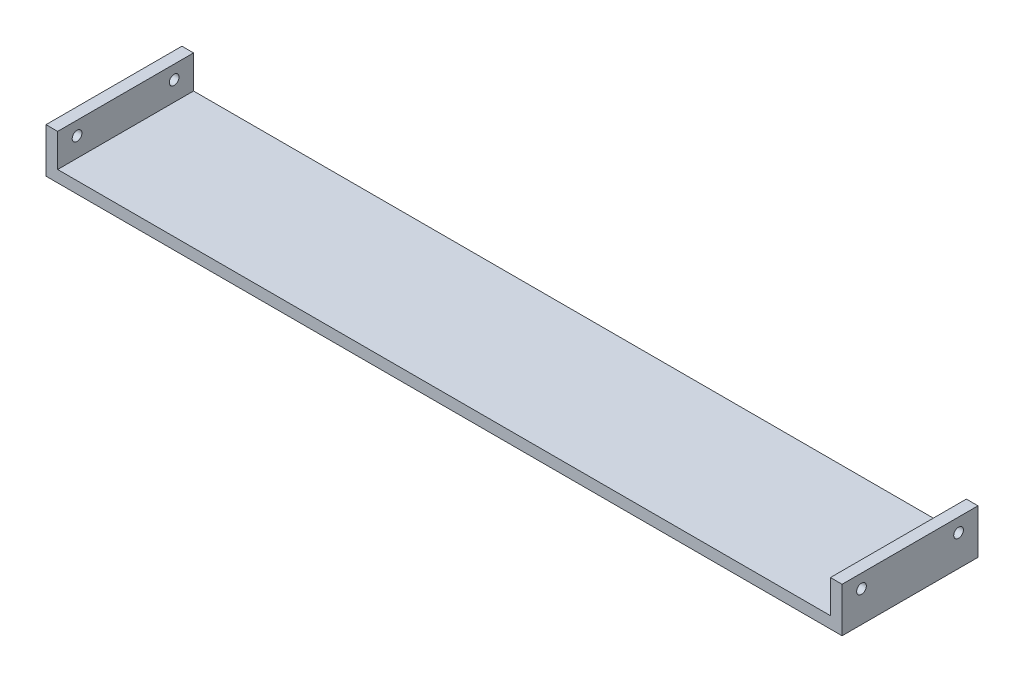
SolidWorks part; units mm, degrees
ref_plane "Front Plane" through (0, 0, 0) normal (0, 0, 1) x (1, 0, 0)
ref_plane "Top Plane" through (0, 0, 0) normal (0, 1, 0) x (1, 0, 0)
ref_plane "Right Plane" through (0, 0, 0) normal (1, 0, 0) x (0, 0, -1)
sketch "Sketch1" plane through (0, 0, 0) normal (0, 1, 0) x (1, 0, 0)
  line L1 (-70.361, 74.6488) -> (339.639, 74.6488)
  line L2 (-70.361, 74.6488) -> (-70.361, 4.6488)
  line L3 (-70.361, 4.6488) -> (339.639, 4.6488)
  line L4 (339.639, 74.6488) -> (339.639, 4.6488)
  dimension "D1" = 70
  dimension "D2" = 410
extrude "Boss-Extrude1" add sketch "Sketch1" along normal blind 6
sketch "Sketch2" plane through (0, 6, 0) normal (0, 1, 0) x (1, 0, 0)
  line L0 (339.639, 74.6488) -> (-70.361, 74.6488) construction
  line L1 (-70.361, 4.6488) -> (-64.361, 4.6488)
  line L2 (-70.361, 4.6488) -> (-70.361, 74.6488)
  line L3 (-70.361, 74.6488) -> (-64.361, 74.6488)
  line L4 (-64.361, 4.6488) -> (-64.361, 74.6488)
  line L5 (-70.361, 4.6488) -> (339.639, 4.6488) construction
  line L6 (339.639, 74.6488) -> (333.639, 74.6488)
  line L7 (339.639, 74.6488) -> (339.639, 4.6488)
  line L8 (339.639, 4.6488) -> (333.639, 4.6488)
  line L9 (333.639, 74.6488) -> (333.639, 4.6488)
  dimension "D1" = 6
  dimension "D2" = 6
extrude "Boss-Extrude2" add sketch "Sketch2" along normal blind 25
sketch "Sketch3" plane through (-70.361, 0, 0) normal (-1, 0, 0) x (0, 0, 1)
  line L0 (-74.6488, 31) -> (-64.6488, 31)
  line L1 (-74.6488, 31) -> (-4.6488, 31) construction
  circle A0 centre (-64.6488, 16) radius 2.5
  circle A1 centre (-14.6488, 16) radius 2.5
extrude "Cut-Extrude1" cut sketch "Sketch3" against normal through all contours A0 | A1
sketch "Sketch4" plane through (339.639, 0, 0) normal (1, 0, 0) x (0, 0, -1)
  line L0 (74.6488, 31) -> (74.6488, 0) construction
  line L1 (4.6488, 31) -> (74.6488, 31)
  line L2 (4.6488, 31) -> (4.6488, 23)
  line L3 (4.6488, 23) -> (74.6488, 23)
  line L4 (74.6488, 31) -> (74.6488, 23)
  dimension "D1" = 8
extrude "Cut-Extrude2" cut sketch "Sketch4" against normal through all
